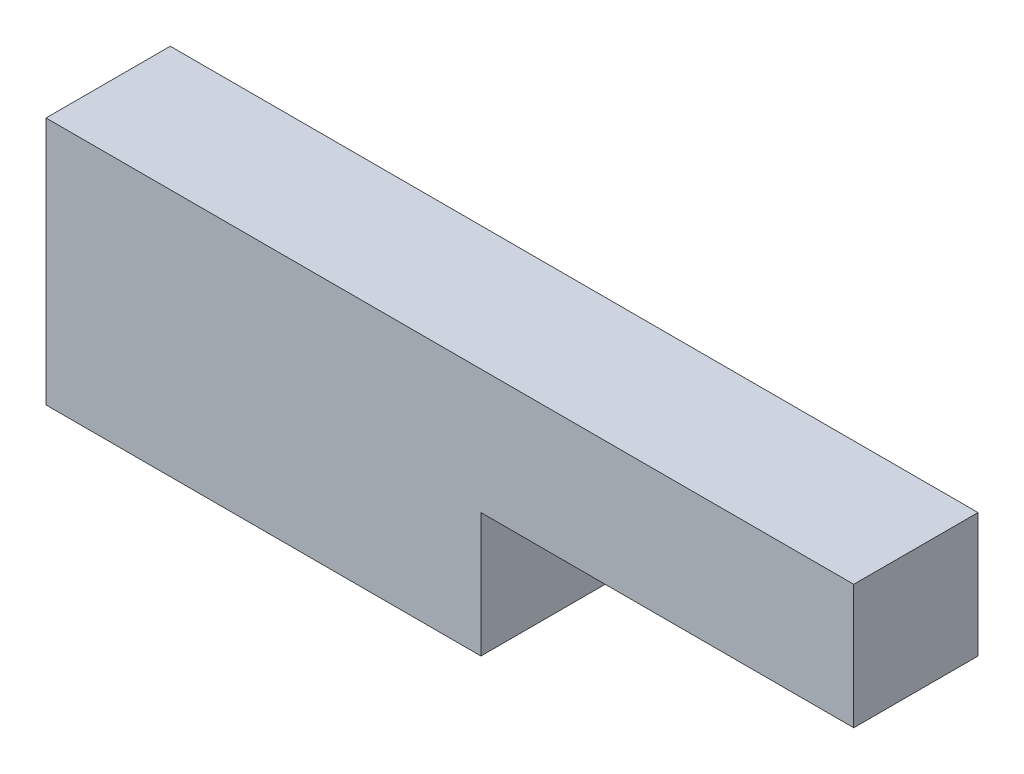
SolidWorks part; units mm, degrees
ref_plane "Front Plane" through (0, 0, 0) normal (0, 0, 1) x (1, 0, 0)
ref_plane "Top Plane" through (0, 0, 0) normal (0, 1, 0) x (1, 0, 0)
ref_plane "Right Plane" through (0, 0, 0) normal (1, 0, 0) x (0, 0, -1)
sketch "Sketch1" plane through (0, 0, 0) normal (0, 0, 1) x (1, 0, 0)
  line L0 (0, 0) -> (0, 101.6)
  line L1 (0, 101.6) -> (330.2, 101.6)
  line L2 (330.2, 101.6) -> (330.2, 50.8)
  line L3 (330.2, 50.8) -> (177.8, 50.8)
  line L4 (177.8, 50.8) -> (177.8, 0)
  line L5 (177.8, 0) -> (0, 0)
  dimension "D1" = 177.8
  dimension "D2" = 50.8
  dimension "D3" = 330.2
  dimension "D4" = 50.8
extrude "Boss-Extrude1" add sketch "Sketch1" along normal blind 50.8
